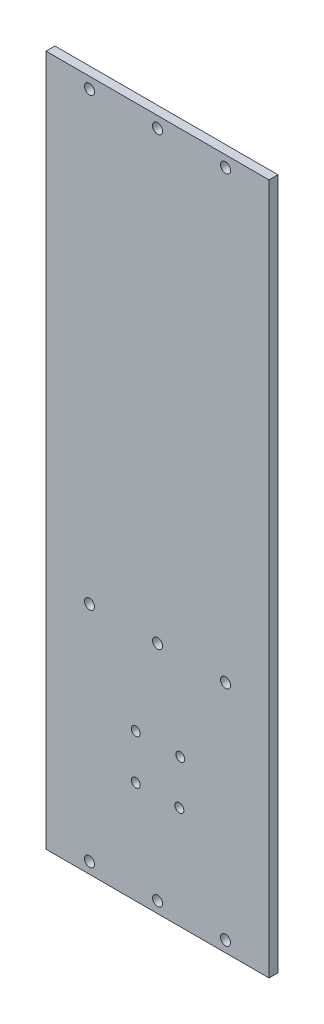
SolidWorks part; units mm, degrees
ref_plane "Piano frontale" through (0, 0, 0) normal (0, 0, 1) x (1, 0, 0)
ref_plane "Piano superiore" through (0, 0, 0) normal (0, 1, 0) x (1, 0, 0)
ref_plane "Piano destro" through (0, 0, 0) normal (1, 0, 0) x (0, 0, -1)
sketch "Schizzo1" plane through (0, 0, 0) normal (0, 0, 1) x (1, 0, 0)
  line L0 (50, 0) -> (50, 310) construction
  line L1 (0, 0) -> (100, 0)
  line L2 (0, 0) -> (0, 310)
  line L3 (0, 310) -> (100, 310)
  line L4 (100, 0) -> (100, 310)
  line L5 (0, 105) -> (100, 105) construction
  line L6 (100, 5) -> (0, 5) construction
  line L7 (40.2076, 66) -> (60.2076, 66) construction
  line L9 (100, 155) -> (0, 155) construction
  circle A0 centre (80.5, 5) radius 2.25
  circle A1 centre (50, 5) radius 2.25
  circle A2 centre (19.5, 5) radius 2.25
  circle A3 centre (19.5, 305) radius 2.25
  circle A4 centre (50, 305) radius 2.25
  circle A5 centre (80.5, 305) radius 2.25
  circle A6 centre (40.2076, 46) radius 2
  circle A7 centre (59.7924, 46) radius 2
  circle A8 centre (40.2076, 66) radius 2
  circle A9 centre (60.2076, 66) radius 2
  circle A10 centre (50, 105) radius 2.25
  circle A11 centre (80.5, 105) radius 2.25
  circle A12 centre (19.5, 105) radius 2.25
  dimension "D4" = 4.5
  dimension "D9" = 4
  dimension "D1" = 100
  dimension "D2" = 310
  dimension "D3" = 5
  dimension "D5" = 30.5
  dimension "D6" = 66
  dimension "D7" = 20
  dimension "D8" = 20
  dimension "D12" = 30.5
  dimension "D13" = 30.5
  dimension "D14" = 105
  dimension "D15" = 5
extrude "Estrusione-Estrusione1" add sketch "Schizzo1" against normal blind 4
